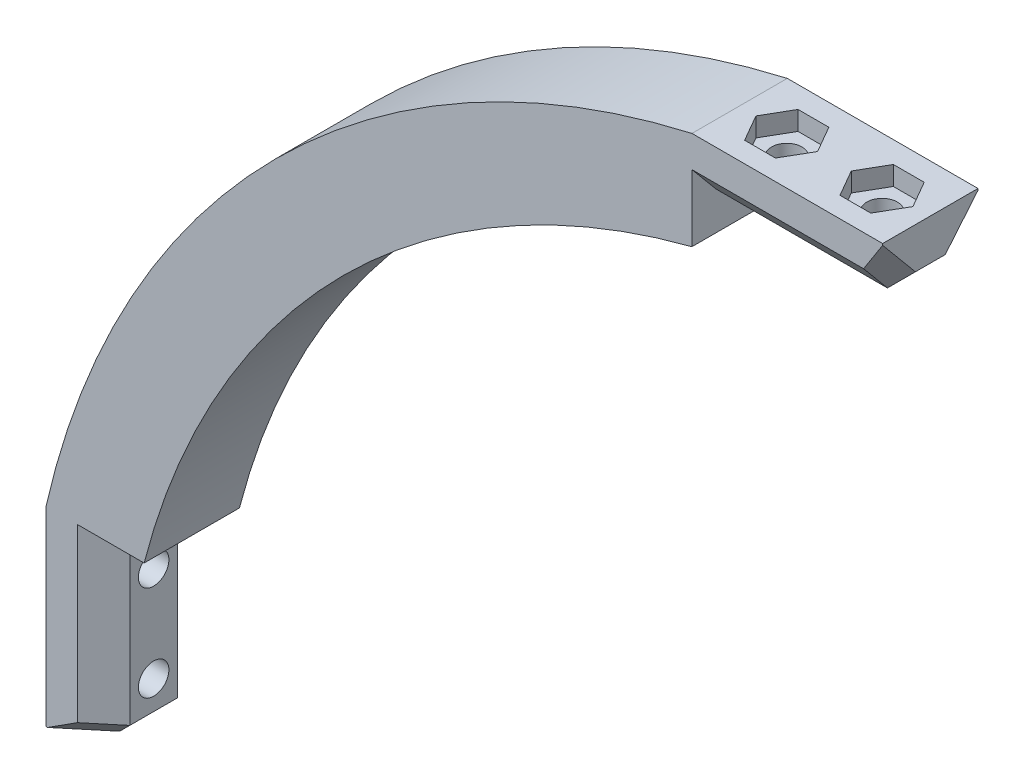
SolidWorks part; units mm, degrees
ref_plane "Plan de face" through (0, 0, 0) normal (0, 0, 1) x (1, 0, 0)
ref_plane "Plan de dessus" through (0, 0, 0) normal (0, 1, 0) x (1, 0, 0)
ref_plane "Plan de droite" through (0, 0, 0) normal (1, 0, 0) x (0, 0, -1)
sketch "Esquisse1" plane through (0, 0, 0) normal (0, 0, 1) x (1, 0, 0)
  line L0 (0, 20) -> (-56.711, 20) construction
  line L1 (-20, 8.5699) -> (-20, 77.4597) construction
  line L5 (-20, 87.7496) -> (0, 87.7496)
  line L7 (-20, 77.4597) -> (0, 77.4597)
  line L8 (0, 87.7496) -> (0, 77.4597)
  line L10 (-77.4597, 20) -> (-77.4597, 0)
  line L11 (-77.4597, 0) -> (-87.7496, 0)
  line L12 (-87.7496, 20) -> (-87.7496, 0)
  arc A0 (-20, 77.4597) -> (-77.4597, 20) centre (0, 0) ccw
  arc A1 (-20, 87.7496) -> (-87.7496, 20) centre (0, 0) ccw
  dimension "D1" = 160
  dimension "D2" = 10
  dimension "D3" = 20
  dimension "D4" = 20
  dimension "D5" = 20
  dimension "D6" = 20
extrude "Boss.-Extru.1" add sketch "Esquisse1" along normal blind 10 contours A1 L12 L11 L10 A0 L7 L8 L5
sketch "Esquisse2" plane through (0, 0, 0) normal (0, -1, 0) x (1, 0, 0)
  line L0 (-84.4597, 10) -> (-77.4597, 10)
  line L1 (-77.4597, 10) -> (-87.7496, 10) construction
  line L2 (-77.4597, 10) -> (-77.4597, 0)
  line L3 (-77.4597, 0) -> (-84.4597, 0)
  line L4 (-77.4597, 0) -> (-87.7496, 0) construction
  line L5 (-84.4597, 0) -> (-81.4597, 2.5)
  line L6 (-81.4597, 2.5) -> (-81.4597, 7.5)
  line L7 (-81.4597, 7.5) -> (-84.4597, 10)
  dimension "D1" = 7
  dimension "D2" = 7
  dimension "D3" = 4
  dimension "D4" = 5
  dimension "D5" = 2.5
extrude "Enlèv. mat.-Extru.1" cut sketch "Esquisse2" against normal blind 20
sketch "Esquisse4" plane through (0, 0, 0) normal (1, 0, 0) x (0, 0, -1)
  line L0 (0, 84.4597) -> (0, 77.4597)
  line L1 (0, 87.7496) -> (0, 77.4597) construction
  line L2 (0, 77.4597) -> (-10, 77.4597)
  line L3 (-10, 77.4597) -> (-10, 84.4597)
  line L4 (-10, 87.7496) -> (-10, 77.4597) construction
  line L5 (-10, 84.4597) -> (-7.5, 81.4597)
  line L6 (-7.5, 81.4597) -> (-2.5, 81.4597)
  line L7 (-2.5, 81.4597) -> (0, 84.4597)
  dimension "D1" = 7
  dimension "D2" = 7
  dimension "D3" = 5
  dimension "D4" = 2.5
  dimension "D5" = 4
extrude "Enlèv. mat.-Extru.2" cut sketch "Esquisse4" against normal blind 20
sketch "Esquisse5" plane through (-81.4597, 0, 0) normal (1, 0, 0) x (0, 0, -1)
  line L0 (-10, 20) -> (-10, 0) construction
  line L1 (-7.5, 0) -> (-2.5, 0) construction
  circle A0 centre (-5, 5) radius 1.6
  circle A1 centre (-5, 15) radius 1.6
  dimension "D1" = 3.2
  dimension "D2" = 3.2
  dimension "D3" = 5
  dimension "D4" = 5
  dimension "D5" = 5
  dimension "D6" = 10
extrude "Enlèv. mat.-Extru.3" cut sketch "Esquisse5" against normal blind 20
sketch "Esquisse6" plane through (0, 81.4597, 0) normal (0, -1, 0) x (1, 0, 0)
  line L0 (0, 2.5) -> (0, 7.5) construction
  circle A0 centre (-5, 5.059) radius 1.6
  circle A1 centre (-15, 5.059) radius 1.6
  dimension "D1" = 3.2
  dimension "D2" = 3.2
  dimension "D3" = 5
  dimension "D4" = 10
extrude "Enlèv. mat.-Extru.4" cut sketch "Esquisse6" against normal blind 20
chamfer "Chanfrein1" distance 2 angle 45 6 edges at (-82.9597, 0, 1.25) (-81.4597, 0, 5) (-82.9597, 0, 8.75) (0, 82.9597, 1.25) (0, 82.9597, 8.75) (0, 81.4597, 5)
sketch "Esquisse7" plane through (-87.7496, 0, 0) normal (-1, 0, 0) x (0, 0, 1)
  line L0 (10, 0) -> (0, 0) construction
  line L1 (2.2, 6.6166) -> (2.2, 3.3834)
  line L2 (2.2, 3.3834) -> (5, 1.7668)
  line L3 (5, 1.7668) -> (7.8, 3.3834)
  line L4 (7.8, 3.3834) -> (7.8, 6.6166)
  line L5 (7.8, 6.6166) -> (5, 8.2332)
  line L6 (5, 8.2332) -> (2.2, 6.6166)
  line L7 (7.8, 16.6166) -> (5, 18.2332)
  line L8 (5, 18.2332) -> (2.2, 16.6166)
  line L9 (2.2, 16.6166) -> (2.2, 13.3834)
  line L10 (2.2, 13.3834) -> (5, 11.7668)
  line L11 (5, 11.7668) -> (7.8, 13.3834)
  line L12 (7.8, 13.3834) -> (7.8, 16.6166)
  circle A0 centre (5, 5) radius 2.8 construction
  circle A1 centre (5, 15) radius 2.8 construction
  dimension "D1" = 5.6
  dimension "D2" = 5.6
  dimension "D3" = 90
  dimension "D4" = 90
extrude "Enlèv. mat.-Extru.5" cut sketch "Esquisse7" against normal blind 2
sketch "Esquisse8" plane through (0, 87.7496, 0) normal (0, 1, 0) x (1, 0, 0)
  line L0 (0, -10) -> (0, 0) construction
  line L1 (-3.3834, -2.259) -> (-6.6166, -2.259)
  line L2 (-6.6166, -2.259) -> (-8.2332, -5.059)
  line L3 (-8.2332, -5.059) -> (-6.6166, -7.859)
  line L4 (-6.6166, -7.859) -> (-3.3834, -7.859)
  line L5 (-3.3834, -7.859) -> (-1.7668, -5.059)
  line L6 (-1.7668, -5.059) -> (-3.3834, -2.259)
  line L8 (-13.3834, -2.259) -> (-16.6166, -2.259)
  line L9 (-16.6166, -2.259) -> (-18.2332, -5.059)
  line L10 (-18.2332, -5.059) -> (-16.6166, -7.859)
  line L11 (-16.6166, -7.859) -> (-13.3834, -7.859)
  line L12 (-13.3834, -7.859) -> (-11.7668, -5.059)
  line L13 (-11.7668, -5.059) -> (-13.3834, -2.259)
  circle A0 centre (-5, -5.059) radius 2.8 construction
  circle A1 centre (-15, -5.059) radius 2.8 construction
  dimension "D1" = 90
  dimension "D2" = 90
  dimension "D3" = 5.6
  dimension "D4" = 5.6
extrude "Enlèv. mat.-Extru.6" cut sketch "Esquisse8" against normal blind 2
